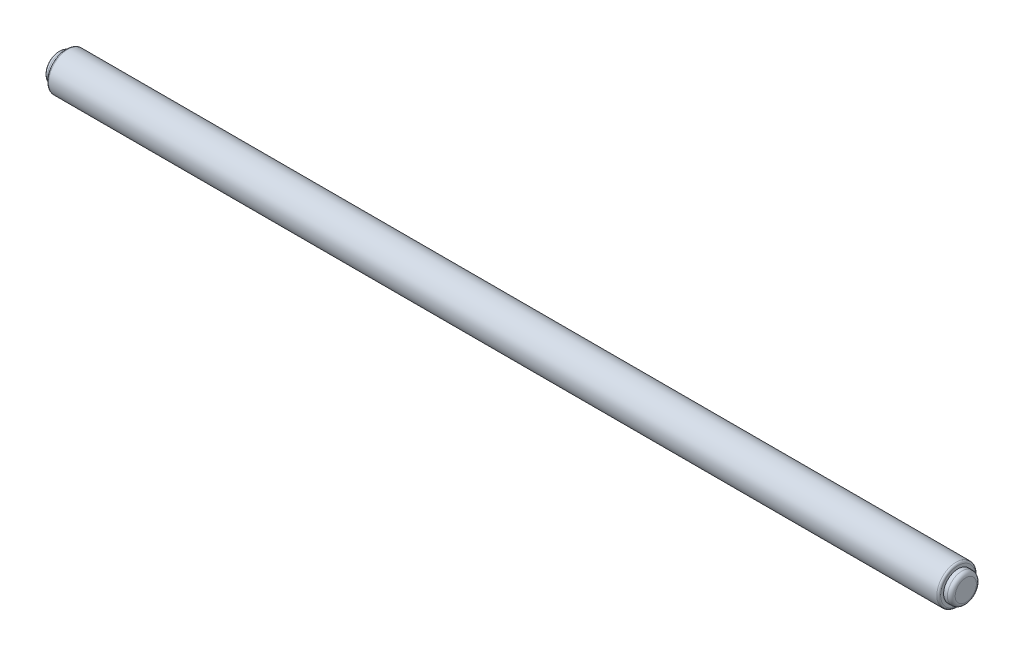
SolidWorks part; units mm, degrees
ref_plane "Ön Düzlem" through (0, 0, 0) normal (0, 0, 1) x (1, 0, 0)
ref_plane "Üst Düzlem" through (0, 0, 0) normal (0, 1, 0) x (1, 0, 0)
ref_plane "Sağ Düzlem" through (0, 0, 0) normal (1, 0, 0) x (0, 0, -1)
sketch "Çizim1" plane through (0, 0, 0) normal (0, 0, 1) x (1, 0, 0)
  line L0 (-235, 0) -> (235, 0) construction
  line L1 (-235, 0) -> (-235, 7.5)
  line L2 (-235, 7.5) -> (-231, 7.5)
  line L3 (-231, 7.5) -> (-231, 10)
  line L4 (-231, 10) -> (231, 10)
  line L5 (231, 10) -> (231, 7.5)
  line L6 (231, 7.5) -> (235, 7.5)
  line L7 (235, 7.5) -> (235, 0)
  line L8 (-235, 0) -> (235, 0)
  point P3 (0, 0)
  dimension "D1" = 470
  dimension "D2" = 7.5
  dimension "D3" = 10
  dimension "D4" = 4
  dimension "D5" = 4
revolve "Döndür1" add sketch "Çizim1" angle 360 about L0
fillet "Radyus1" radius 1 2 edges at (231, -10, 0) (-231, -10, 0)
fillet "Radyus2" radius 2 2 edges at (235, -7.5, 0) (-235, -7.5, 0)
